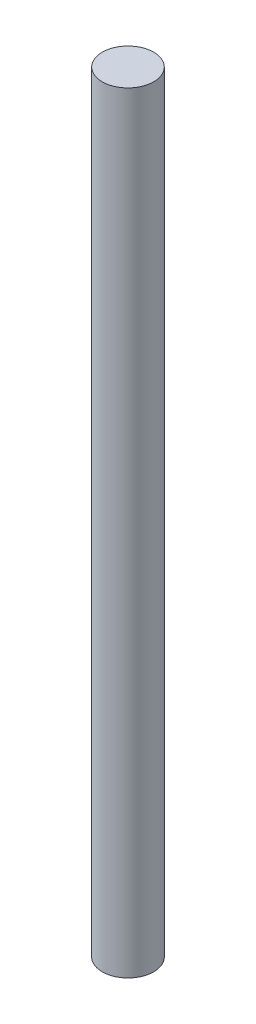
SolidWorks part; units mm, degrees
ref_plane "前视基准面" through (0, 0, 0) normal (0, 0, 1) x (1, 0, 0)
ref_plane "上视基准面" through (0, 0, 0) normal (0, 1, 0) x (1, 0, 0)
ref_plane "右视基准面" through (0, 0, 0) normal (1, 0, 0) x (0, 0, -1)
sketch "草图1" plane through (0, 0, 0) normal (0, 1, 0) x (1, 0, 0)
  circle A0 centre (0, 0) radius 1
  dimension "D1" = 2
extrude "凸台-拉伸1" add sketch "草图1" along normal blind 30
